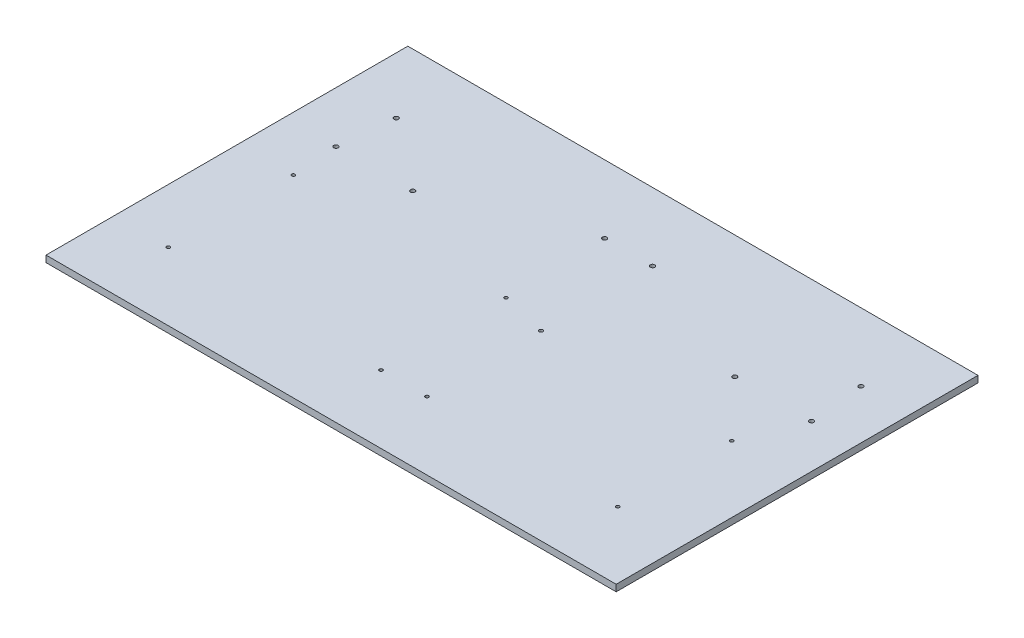
SolidWorks part; units mm, degrees
material "PET"
ref_plane "Front Plane" through (0, 0, 0) normal (0, 0, 1) x (1, 0, 0)
ref_plane "Top Plane" through (0, 0, 0) normal (0, 1, 0) x (1, 0, 0)
ref_plane "Right Plane" through (0, 0, 0) normal (1, 0, 0) x (0, 0, -1)
sketch "Sketch1" plane through (0, 0, 0) normal (0, 1, 0) x (1, 0, 0)
  line L1 (0, 0) -> (520, 0)
  line L2 (0, 0) -> (0, 330)
  line L3 (0, 330) -> (520, 330)
  line L4 (520, 0) -> (520, 330)
  dimension "D1" = 330
  dimension "D2" = 520
extrude "Boss-Extrude1" add sketch "Sketch1" along normal blind 6
sketch "Sketch2" plane through (0, 6, 0) normal (0, 1, 0) x (1, 0, 0)
  circle A0 centre (475.2326, 267.9287) radius 2
  circle A1 centre (480.2326, 217.9287) radius 2
  circle A2 centre (410.2326, 217.9287) radius 2
  circle A3 centre (285.2326, 267.9287) radius 2
  circle A4 centre (241.5447, 267.9287) radius 2
  circle A5 centre (51.5447, 267.9287) radius 2
  circle A6 centre (46.5447, 217.9287) radius 2
  circle A7 centre (116.5447, 217.9287) radius 2
  circle A8 centre (459.4913, 165.9594) radius 1.5
  circle A9 centre (459.4913, 61.9594) radius 1.5
  circle A10 centre (285.4913, 61.9594) radius 1.5
  circle A11 centre (285.4913, 165.9594) radius 1.6593
  circle A12 centre (243.5639, 175.9594) radius 1.5
  circle A13 centre (243.5639, 61.9594) radius 1.5
  circle A14 centre (49.5639, 61.9594) radius 1.5
  circle A15 centre (49.5639, 175.9594) radius 1.5
extrude "Cut-Extrude1" cut sketch "Sketch2" against normal blind 10
